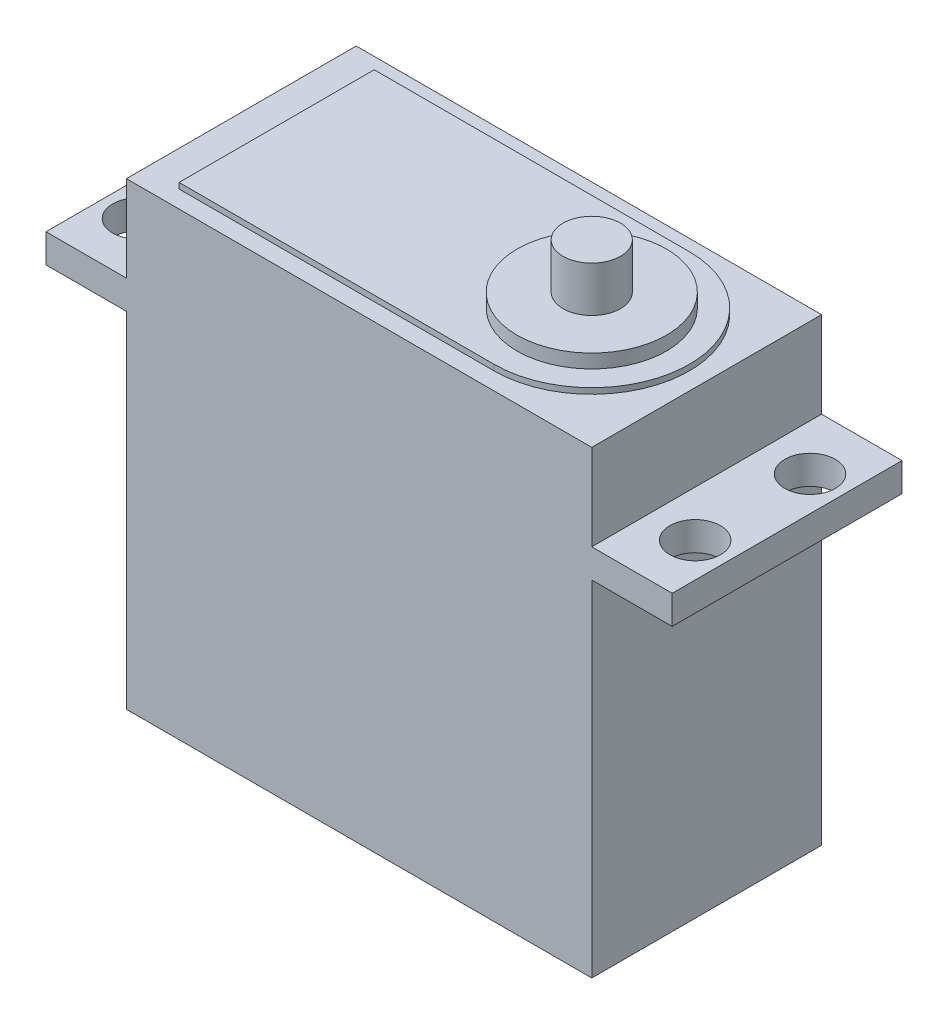
SolidWorks part; units mm, degrees
ref_plane "前视基准面" through (0, 0, 0) normal (0, 0, 1) x (1, 0, 0)
ref_plane "上视基准面" through (0, 0, 0) normal (0, 1, 0) x (1, 0, 0)
ref_plane "右视基准面" through (0, 0, 0) normal (1, 0, 0) x (0, 0, -1)
other "Configuration Table"
sketch "草图1" plane through (0, 0, 0) normal (0, 1, 0) x (1, 0, 0)
  line L1 (0, 0) -> (40.5, 0)
  line L2 (0, 0) -> (0, -20)
  line L3 (0, -20) -> (40.5, -20)
  line L4 (40.5, 0) -> (40.5, -20)
  dimension "D1" = 40.5
  dimension "D2" = 20
extrude "凸台-拉伸1" add sketch "草图1" along normal blind 30
sketch "草图2" plane through (0, 30, 0) normal (0, 1, 0) x (1, 0, 0)
  line L0 (0, -20) -> (40.5, -20) construction
  line L1 (-7, 0) -> (47.5, 0)
  line L2 (-7, 0) -> (-7, -20)
  line L3 (-7, -20) -> (47.5, -20)
  line L4 (47.5, 0) -> (47.5, -20)
  line L5 (40.5, 0) -> (0, 0) construction
  line L6 (0, 0) -> (0, -20) construction
  dimension "D1" = 54.5
  dimension "D2" = 7
extrude "凸台-拉伸2" add sketch "草图2" along normal blind 2.5
sketch "草图3" plane through (0, 32.5, 0) normal (0, 1, 0) x (1, 0, 0)
  line L0 (-7, -20) -> (47.5, -20) construction
  line L1 (0, 0) -> (40.5, 0)
  line L2 (0, 0) -> (0, -20)
  line L3 (0, -20) -> (40.5, -20)
  line L4 (40.5, 0) -> (40.5, -20)
  dimension "D1" = 40.5
extrude "凸台-拉伸3" add sketch "草图3" along normal blind 7.5
sketch "草图4" plane through (0, 40, 0) normal (0, 1, 0) x (1, 0, 0)
  line L0 (40.5, -20) -> (40.5, 0) construction
  line L1 (30.5, -10) -> (40.5, -10) construction
  line L2 (30.5, -18.4922) -> (3.073, -18.4922)
  line L3 (30.5, -18.4922) -> (30.5, -1.5078)
  line L4 (30.5, -1.5078) -> (3.073, -1.5078)
  line L5 (3.073, -18.4922) -> (3.073, -1.5078)
  circle A0 centre (30.5, -10) radius 8.4922
  point P8 (38.5, -1.5078)
  dimension "D1" = 10
extrude "凸台-拉伸4" add sketch "草图4" along normal blind 0.5 contours A0 L4 L5 L2 | L3 A0 | L1 L3 A0 | L3 L1 A0
sketch "草图5" plane through (0, 40.5, 0) normal (0, 1, 0) x (1, 0, 0)
  circle A0 centre (30.5, -10) radius 6.5
  dimension "D1" = 13
extrude "凸台-拉伸5" add sketch "草图5" along normal blind 1.2
sketch "草图6" plane through (0, 41.7, 0) normal (0, 1, 0) x (1, 0, 0)
  circle A0 centre (30.5, -10) radius 2.5
  dimension "D1" = 5
extrude "凸台-拉伸6" add sketch "草图6" along normal blind 3.95
sketch "草图7" plane through (0, 32.5, 0) normal (0, 1, 0) x (1, 0, 0)
  line L1 (-4, -5) -> (-4, -15) construction
  line L2 (-4, -15) -> (44.5, -15) construction
  line L3 (44.5, -15) -> (44.5, -5) construction
  line L4 (44.5, -5) -> (-4, -5) construction
  line L5 (0, 0) -> (-7, 0) construction
  line L7 (20.25, 0) -> (20.25, -20) construction
  line L8 (40.5, 0) -> (0, 0) construction
  line L9 (0, -20) -> (40.5, -20) construction
  circle A0 centre (44.5, -5) radius 2.2
  circle A1 centre (44.5, -15) radius 2.2
  circle A2 centre (-4, -5) radius 2.2
  circle A3 centre (-4, -15) radius 2.2
  dimension "D2" = 4.4
  dimension "D1" = 48.5
  dimension "D3" = 10
  dimension "D4" = 5
extrude "切除-拉伸1" cut sketch "草图7" against normal blind 3.95
